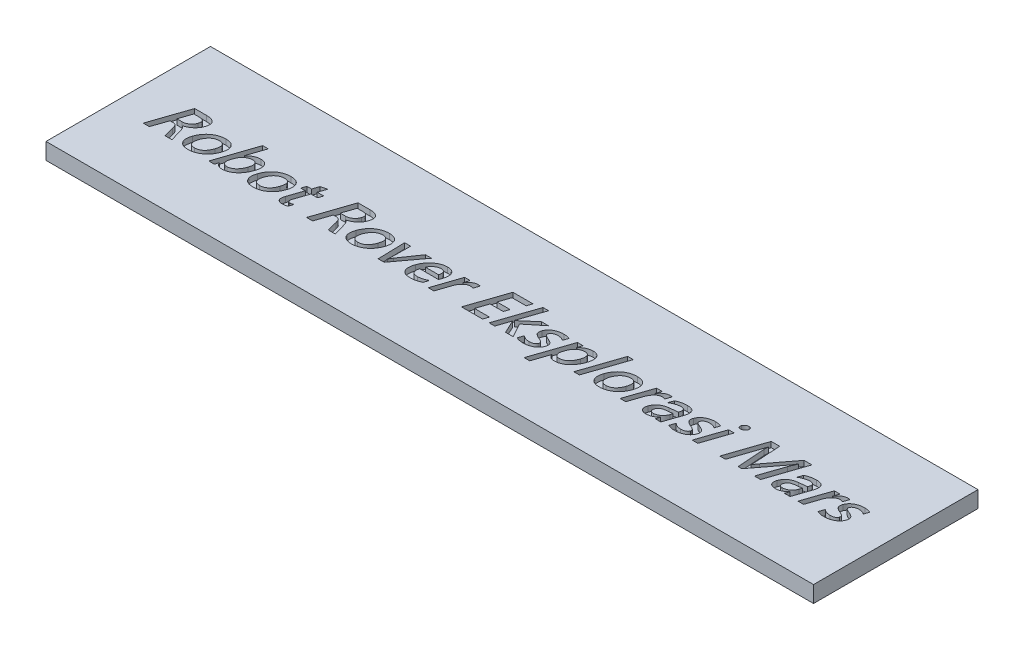
SolidWorks part; units mm, degrees
ref_plane "Front Plane" through (0, 0, 0) normal (0, 0, 1) x (1, 0, 0)
ref_plane "Top Plane" through (0, 0, 0) normal (0, 1, 0) x (1, 0, 0)
ref_plane "Right Plane" through (0, 0, 0) normal (1, 0, 0) x (0, 0, -1)
sketch "Sketch1" plane through (0, 0, 0) normal (0, 1, 0) x (1, 0, 0)
  line L1 (-70, 15) -> (70, 15)
  line L2 (-70, 15) -> (-70, -15)
  line L3 (-70, -15) -> (70, -15)
  line L4 (70, 15) -> (70, -15)
  line L5 (-70, 15) -> (70, -15) construction
  line L6 (-70, -15) -> (70, 15) construction
  point P0 (0, 0)
  dimension "D1" = 30
  dimension "D2" = 140
extrude "Boss-Extrude1" add sketch "Sketch1" along normal blind 3
sketch "Sketch2" plane through (0, 3, 0) normal (0, 1, 0) x (1, 0, 0)
  text T0 "Robot Rover Eksplorasi Mars" font "@Microsoft JhengHei" height 7
extrude "Cut-Extrude1" cut sketch "Sketch2" against normal blind 1
